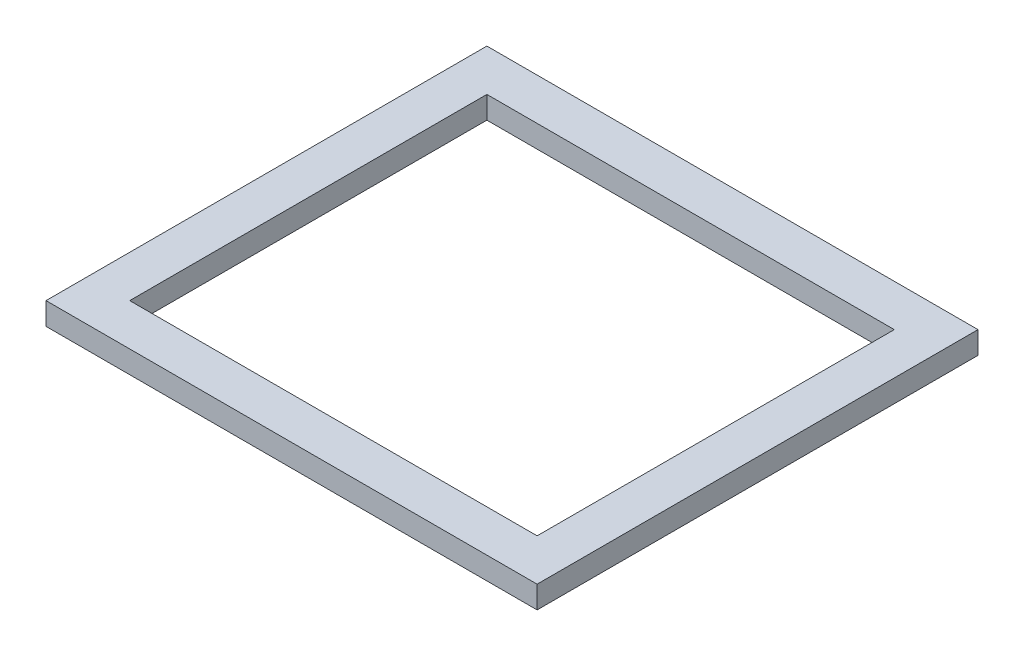
SolidWorks part; units mm, degrees
ref_plane "Front Plane" through (0, 0, 0) normal (0, 0, 1) x (1, 0, 0)
ref_plane "Top Plane" through (0, 0, 0) normal (0, 1, 0) x (1, 0, 0)
ref_plane "Right Plane" through (0, 0, 0) normal (1, 0, 0) x (0, 0, -1)
sketch "Sketch1" plane through (0, 0, 0) normal (0, 1, 0) x (1, 0, 0)
  line L1 (-8.8, 7.9) -> (8.8, 7.9)
  line L2 (-8.8, 7.9) -> (-8.8, -7.9)
  line L3 (-8.8, -7.9) -> (8.8, -7.9)
  line L4 (8.8, 7.9) -> (8.8, -7.9)
  line L5 (-8.8, 7.9) -> (8.8, -7.9) construction
  line L6 (-8.8, -7.9) -> (8.8, 7.9) construction
  point P4 (0, 0)
  point P5 (0, 0)
  dimension "D1" = 17.6
  dimension "D2" = 15.8
extrude "Extrude-Thin1" add sketch "Sketch1" along normal blind 0.8 thin
